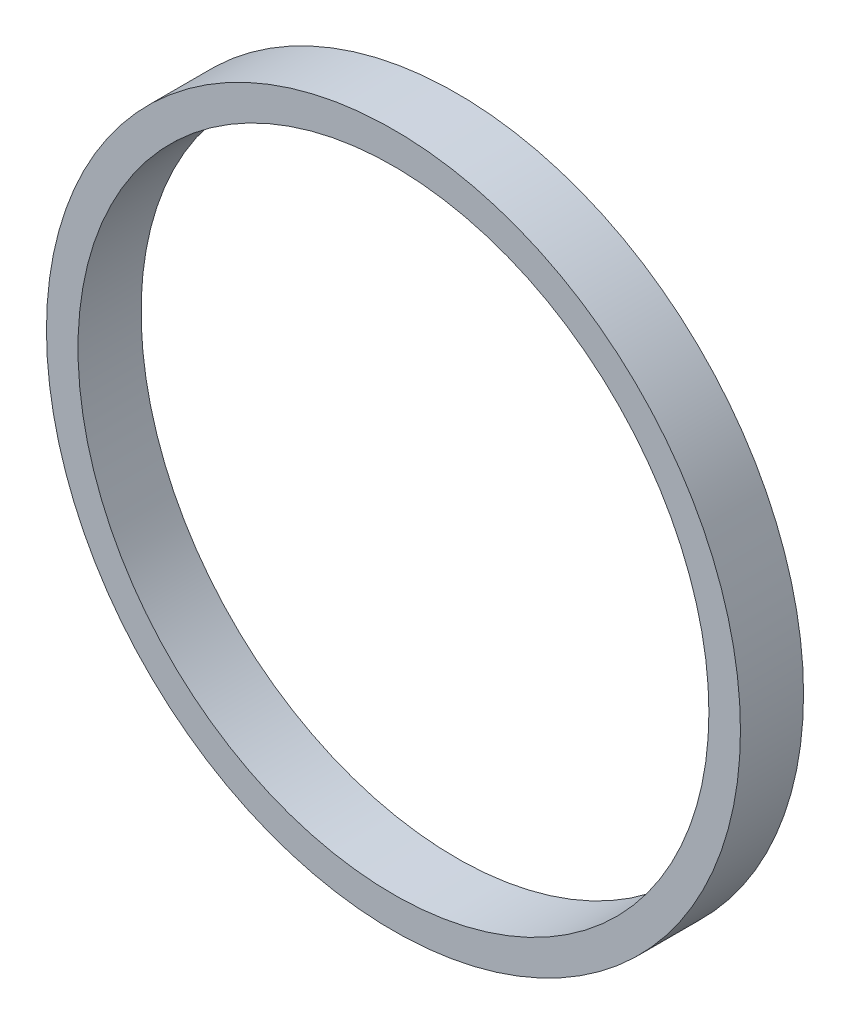
SolidWorks part; units mm, degrees
ref_plane "前视基准面" through (0, 0, 0) normal (0, 0, 1) x (1, 0, 0)
ref_plane "上视基准面" through (0, 0, 0) normal (0, 1, 0) x (1, 0, 0)
ref_plane "右视基准面" through (0, 0, 0) normal (1, 0, 0) x (0, 0, -1)
other "Configuration Table"
sketch "草图1" plane through (0, 0, 0) normal (0, 0, 1) x (1, 0, 0)
  line L0 (50, 0) -> (55, 0) construction
  circle A0 centre (0, 0) radius 50
  circle A1 centre (0, 0) radius 55
  dimension "D1" = 100
  dimension "D2" = 5
extrude "凸台-拉伸1" add sketch "草图1" along normal blind 10
